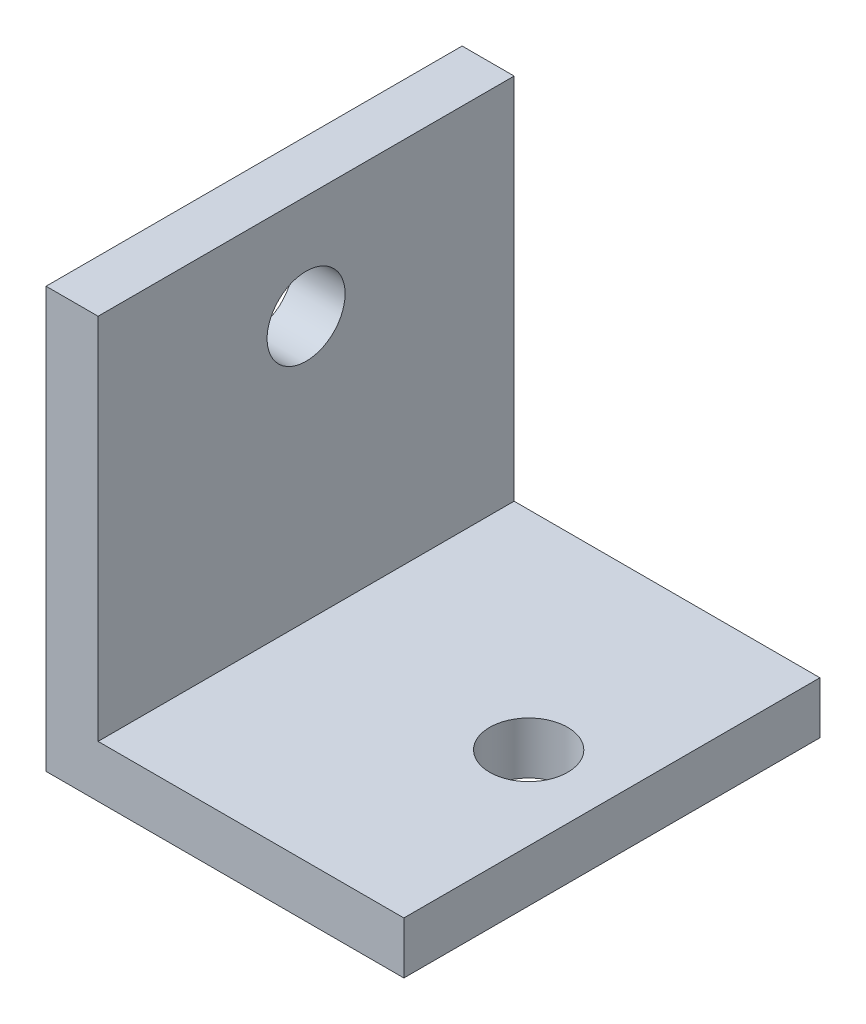
SolidWorks part; units mm, degrees
material "6061 Alloy"
ref_plane "Front Plane" through (0, 0, 0) normal (0, 0, 1) x (1, 0, 0)
ref_plane "Top Plane" through (0, 0, 0) normal (0, 1, 0) x (1, 0, 0)
ref_plane "Right Plane" through (0, 0, 0) normal (1, 0, 0) x (0, 0, -1)
sketch "Sketch1" plane through (0, 0, 0) normal (0, 0, 1) x (1, 0, 0)
  line L0 (0, 0) -> (0, 25.654)
  line L1 (0, 0) -> (21.844, 0)
  line L2 (21.844, 0) -> (21.844, 3.175)
  line L3 (0, 25.654) -> (3.175, 25.654)
  line L4 (3.175, 25.654) -> (3.175, 3.175)
  line L5 (3.175, 3.175) -> (21.844, 3.175)
extrude "Boss-Extrude1" add sketch "Sketch1" along normal blind 25.4
sketch "Sketch2" plane through (3.175, 0, 0) normal (1, 0, 0) x (0, 0, -1)
  line L0 (-25.4, 25.654) -> (0, 25.654) construction
  circle A0 centre (-12.7, 19.304) radius 2.3813
  dimension "D1" = 6.35
extrude "Cut-Extrude1" cut sketch "Sketch2" against normal through all contours A0
sketch "Sketch3" plane through (0, 3.175, 0) normal (0, 1, 0) x (1, 0, 0)
  line L0 (21.844, -25.4) -> (21.844, 0) construction
  circle A0 centre (16.764, -12.7) radius 2.3813
  dimension "D1" = 4.7625
  dimension "D2" = 5.08
extrude "Cut-Extrude2" cut sketch "Sketch3" against normal through all
